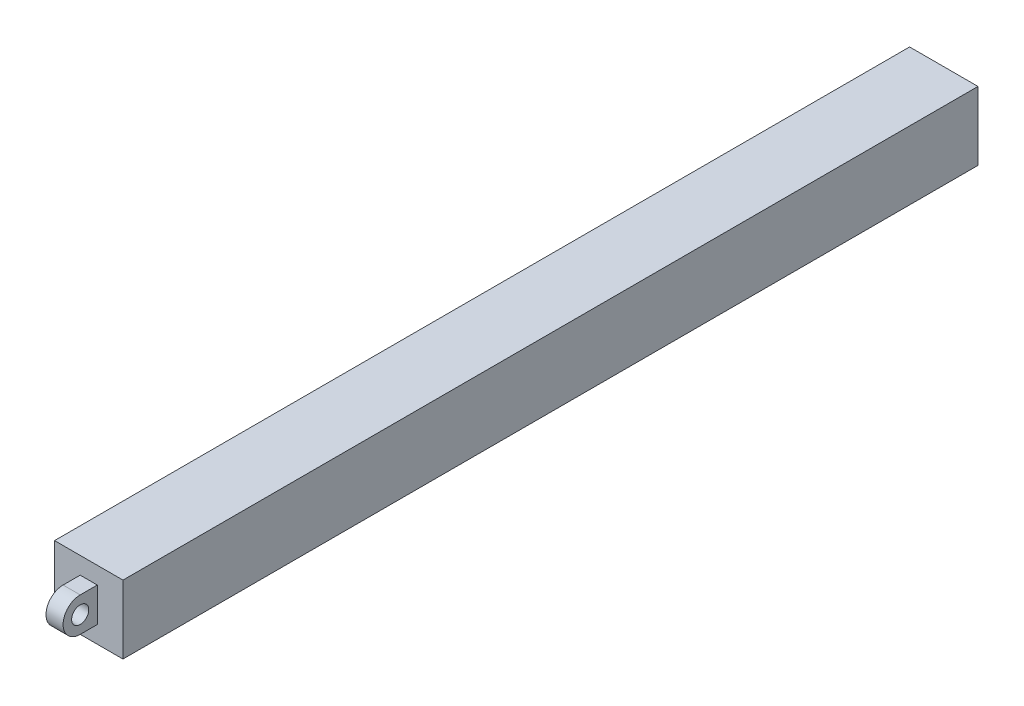
SolidWorks part; units mm, degrees
ref_plane "정면" through (0, 0, 0) normal (0, 0, 1) x (1, 0, 0)
ref_plane "윗면" through (0, 0, 0) normal (0, 1, 0) x (1, 0, 0)
ref_plane "우측면" through (0, 0, 0) normal (1, 0, 0) x (0, 0, -1)
sketch "스케치2" plane through (0, 0, 0) normal (1, 0, 0) x (0, 0, -1)
  line L0 (0, 5) -> (0, -5) construction
  line L1 (-62.5, 5) -> (62.5, 5)
  line L2 (-62.5, 5) -> (-62.5, -5)
  line L3 (-62.5, -5) -> (62.5, -5)
  line L4 (62.5, 5) -> (62.5, -5)
  line L5 (-62.5, 0) -> (62.5, 0) construction
  dimension "D1" = 10
  dimension "D2" = 125
extrude "보스-돌출1" add sketch "스케치2" along normal mid plane 10
sketch "스케치3" plane through (0, 0, 0) normal (1, 0, 0) x (0, 0, -1)
  line L0 (-62.5, 5) -> (-62.5, -5) construction
  line L1 (-65, 2.5) -> (-62.5, 2.5)
  line L2 (0, 0) -> (-168.2672, 0) construction
  line L3 (-65, -2.5) -> (-62.5, -2.5)
  line L4 (-62.5, 2.5) -> (-62.5, -2.5)
  arc A0 (-65, 2.5) -> (-65, -2.5) centre (-65, 0) ccw
  circle A1 centre (-65, 0) radius 1.25
  dimension "D3" = 2.5
  dimension "D1" = 5
  dimension "D2" = 2.5
extrude "보스-돌출2" add sketch "스케치3" along normal mid plane 2.5
